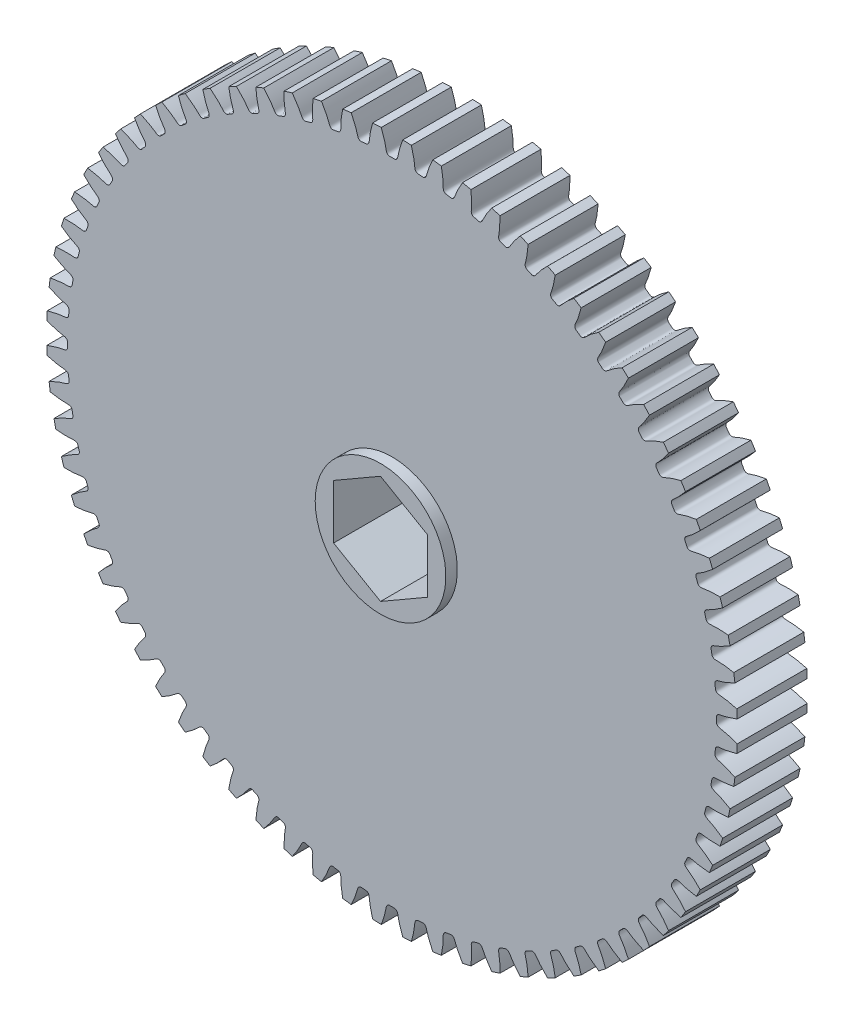
SolidWorks part; units mm, degrees
ref_plane "Front Plane" through (0, 0, 0) normal (0, 0, 1) x (1, 0, 0)
ref_plane "Top Plane" through (0, 0, 0) normal (0, 1, 0) x (1, 0, 0)
ref_plane "Right Plane" through (0, 0, 0) normal (1, 0, 0) x (0, 0, -1)
ref_plane "Plane1" through (0, 0, -4.7625) normal (0, 0, -1) x (-1, 0, 0)
sketch "Sketch1" plane through (0, 0, -4.7625) normal (0, 0, -1) x (-1, 0, 0)
  arc A0 (-46.916, 2.6363) -> (-46.9672, 1.4627) centre (0, 0) ccw
  arc A1 (-46.9672, -1.4627) -> (-46.916, -2.6363) centre (0, 0) ccw
  arc A2 (-46.661, -5.5506) -> (-46.5077, -6.7153) centre (0, 0) ccw
  arc A3 (-45.9997, -9.5963) -> (-45.7454, -10.7431) centre (0, 0) ccw
  arc A4 (-44.9883, -13.5689) -> (-44.635, -14.6892) centre (0, 0) ccw
  arc A5 (-43.6345, -17.4382) -> (-43.1849, -18.5235) centre (0, 0) ccw
  arc A6 (-41.9486, -21.1749) -> (-41.4062, -22.2169) centre (0, 0) ccw
  arc A7 (-39.9435, -24.7504) -> (-39.3123, -25.7411) centre (0, 0) ccw
  arc A8 (-37.6343, -28.1375) -> (-36.9192, -29.0694) centre (0, 0) ccw
  arc A9 (-35.0388, -31.3105) -> (-34.2451, -32.1765) centre (0, 0) ccw
  arc A10 (-32.1765, -34.2451) -> (-31.3105, -35.0388) centre (0, 0) ccw
  arc A11 (-29.0694, -36.9192) -> (-28.1375, -37.6343) centre (0, 0) ccw
  arc A12 (-25.7411, -39.3123) -> (-24.7504, -39.9435) centre (0, 0) ccw
  arc A13 (-22.2169, -41.4062) -> (-21.1749, -41.9486) centre (0, 0) ccw
  arc A14 (-18.5235, -43.1849) -> (-17.4382, -43.6345) centre (0, 0) ccw
  arc A15 (-14.6892, -44.635) -> (-13.5689, -44.9883) centre (0, 0) ccw
  arc A16 (-10.7431, -45.7454) -> (-9.5963, -45.9997) centre (0, 0) ccw
  arc A17 (-6.7153, -46.5077) -> (-5.5506, -46.661) centre (0, 0) ccw
  arc A18 (-2.6363, -46.916) -> (-1.4627, -46.9672) centre (0, 0) ccw
  arc A19 (1.4627, -46.9672) -> (2.6363, -46.916) centre (0, 0) ccw
  arc A20 (5.5506, -46.661) -> (6.7153, -46.5077) centre (0, 0) ccw
  arc A21 (9.5963, -45.9997) -> (10.7431, -45.7454) centre (0, 0) ccw
  arc A22 (13.5689, -44.9883) -> (14.6892, -44.635) centre (0, 0) ccw
  arc A23 (17.4382, -43.6345) -> (18.5235, -43.1849) centre (0, 0) ccw
  arc A24 (21.1749, -41.9486) -> (22.2169, -41.4062) centre (0, 0) ccw
  arc A25 (24.7504, -39.9435) -> (25.7411, -39.3123) centre (0, 0) ccw
  arc A26 (28.1375, -37.6343) -> (29.0694, -36.9192) centre (0, 0) ccw
  arc A27 (31.3105, -35.0388) -> (32.1765, -34.2451) centre (0, 0) ccw
  arc A28 (34.2451, -32.1765) -> (35.0388, -31.3105) centre (0, 0) ccw
  arc A29 (36.9192, -29.0694) -> (37.6343, -28.1375) centre (0, 0) ccw
  arc A30 (39.3123, -25.7411) -> (39.9435, -24.7504) centre (0, 0) ccw
  arc A31 (41.4062, -22.2169) -> (41.9486, -21.1749) centre (0, 0) ccw
  arc A32 (43.1849, -18.5235) -> (43.6345, -17.4382) centre (0, 0) ccw
  arc A33 (44.635, -14.6892) -> (44.9883, -13.5689) centre (0, 0) ccw
  arc A34 (45.7454, -10.7431) -> (45.9997, -9.5963) centre (0, 0) ccw
  arc A35 (46.5077, -6.7153) -> (46.661, -5.5506) centre (0, 0) ccw
  arc A36 (46.916, -2.6363) -> (46.9672, -1.4627) centre (0, 0) ccw
  arc A37 (46.9672, 1.4627) -> (46.916, 2.6363) centre (0, 0) ccw
  arc A38 (46.661, 5.5506) -> (46.5077, 6.7153) centre (0, 0) ccw
  arc A39 (45.9997, 9.5963) -> (45.7454, 10.7431) centre (0, 0) ccw
  arc A40 (44.9883, 13.5689) -> (44.635, 14.6892) centre (0, 0) ccw
  arc A41 (43.6345, 17.4382) -> (43.1849, 18.5235) centre (0, 0) ccw
  arc A42 (41.9486, 21.1749) -> (41.4062, 22.2169) centre (0, 0) ccw
  arc A43 (39.9435, 24.7504) -> (39.3123, 25.7411) centre (0, 0) ccw
  arc A44 (37.6343, 28.1375) -> (36.9192, 29.0694) centre (0, 0) ccw
  arc A45 (35.0388, 31.3105) -> (34.2451, 32.1765) centre (0, 0) ccw
  arc A46 (32.1765, 34.2451) -> (31.3105, 35.0388) centre (0, 0) ccw
  arc A47 (29.0694, 36.9192) -> (28.1375, 37.6343) centre (0, 0) ccw
  arc A48 (25.7411, 39.3123) -> (24.7504, 39.9435) centre (0, 0) ccw
  arc A49 (22.2169, 41.4062) -> (21.1749, 41.9486) centre (0, 0) ccw
  arc A50 (18.5235, 43.1849) -> (17.4382, 43.6345) centre (0, 0) ccw
  arc A51 (14.6892, 44.635) -> (13.5689, 44.9883) centre (0, 0) ccw
  arc A52 (10.7431, 45.7454) -> (9.5963, 45.9997) centre (0, 0) ccw
  arc A53 (6.7153, 46.5077) -> (5.5506, 46.661) centre (0, 0) ccw
  arc A54 (2.6363, 46.916) -> (1.4627, 46.9672) centre (0, 0) ccw
  arc A55 (-1.4627, 46.9672) -> (-2.6363, 46.916) centre (0, 0) ccw
  arc A56 (-5.5506, 46.661) -> (-6.7153, 46.5077) centre (0, 0) ccw
  arc A57 (-9.5963, 45.9997) -> (-10.7431, 45.7454) centre (0, 0) ccw
  arc A58 (-13.5689, 44.9883) -> (-14.6892, 44.635) centre (0, 0) ccw
  arc A59 (-17.4382, 43.6345) -> (-18.5235, 43.1849) centre (0, 0) ccw
  arc A60 (-21.1749, 41.9486) -> (-22.2169, 41.4062) centre (0, 0) ccw
  arc A61 (-24.7504, 39.9435) -> (-25.7411, 39.3123) centre (0, 0) ccw
  arc A62 (-28.1375, 37.6343) -> (-29.0694, 36.9192) centre (0, 0) ccw
  arc A63 (-31.3105, 35.0388) -> (-32.1765, 34.2451) centre (0, 0) ccw
  arc A64 (-34.2451, 32.1765) -> (-35.0388, 31.3105) centre (0, 0) ccw
  arc A65 (-36.9192, 29.0694) -> (-37.6343, 28.1375) centre (0, 0) ccw
  arc A66 (-39.3123, 25.7411) -> (-39.9435, 24.7504) centre (0, 0) ccw
  arc A67 (-41.4062, 22.2169) -> (-41.9486, 21.1749) centre (0, 0) ccw
  arc A68 (-43.1849, 18.5235) -> (-43.6345, 17.4382) centre (0, 0) ccw
  arc A69 (-44.635, 14.6892) -> (-44.9883, 13.5689) centre (0, 0) ccw
  arc A70 (-45.7454, 10.7431) -> (-45.9997, 9.5963) centre (0, 0) ccw
  arc A71 (-46.5077, 6.7153) -> (-46.661, 5.5506) centre (0, 0) ccw
  spline S0 degree 3 number of poles 73 (-46.9672, -1.4627) -> (-46.9672, 1.4627)
  spline S1 degree 3 number of poles 73 (-46.661, -5.5506) -> (-46.916, -2.6363)
  spline S2 degree 3 number of poles 73 (-45.9997, -9.5963) -> (-46.5077, -6.7153)
  spline S3 degree 3 number of poles 73 (-44.9883, -13.5689) -> (-45.7454, -10.7431)
  spline S4 degree 3 number of poles 73 (-43.6345, -17.4382) -> (-44.635, -14.6892)
  spline S5 degree 3 number of poles 73 (-41.9486, -21.1749) -> (-43.1849, -18.5235)
  spline S6 degree 3 number of poles 73 (-39.9435, -24.7504) -> (-41.4062, -22.2169)
  spline S7 degree 3 number of poles 73 (-37.6343, -28.1375) -> (-39.3123, -25.7411)
  spline S8 degree 3 number of poles 73 (-35.0388, -31.3105) -> (-36.9192, -29.0694)
  spline S9 degree 3 number of poles 73 (-32.1765, -34.2451) -> (-34.2451, -32.1765)
  spline S10 degree 3 number of poles 73 (-29.0694, -36.9192) -> (-31.3105, -35.0388)
  spline S11 degree 3 number of poles 73 (-25.7411, -39.3123) -> (-28.1375, -37.6343)
  spline S12 degree 3 number of poles 73 (-22.2169, -41.4062) -> (-24.7504, -39.9435)
  spline S13 degree 3 number of poles 73 (-18.5235, -43.1849) -> (-21.1749, -41.9486)
  spline S14 degree 3 number of poles 73 (-14.6892, -44.635) -> (-17.4382, -43.6345)
  spline S15 degree 3 number of poles 73 (-10.7431, -45.7454) -> (-13.5689, -44.9883)
  spline S16 degree 3 number of poles 73 (-6.7153, -46.5077) -> (-9.5963, -45.9997)
  spline S17 degree 3 number of poles 73 (-2.6363, -46.916) -> (-5.5506, -46.661)
  spline S18 degree 3 number of poles 73 (1.4627, -46.9672) -> (-1.4627, -46.9672)
  spline S19 degree 3 number of poles 73 (5.5506, -46.661) -> (2.6363, -46.916)
  spline S20 degree 3 number of poles 73 (9.5963, -45.9997) -> (6.7153, -46.5077)
  spline S21 degree 3 number of poles 73 (13.5689, -44.9883) -> (10.7431, -45.7454)
  spline S22 degree 3 number of poles 73 (17.4382, -43.6345) -> (14.6892, -44.635)
  spline S23 degree 3 number of poles 73 (21.1749, -41.9486) -> (18.5235, -43.1849)
  spline S24 degree 3 number of poles 73 (24.7504, -39.9435) -> (22.2169, -41.4062)
  spline S25 degree 3 number of poles 73 (28.1375, -37.6343) -> (25.7411, -39.3123)
  spline S26 degree 3 number of poles 73 (31.3105, -35.0388) -> (29.0694, -36.9192)
  spline S27 degree 3 number of poles 73 (34.2451, -32.1765) -> (32.1765, -34.2451)
  spline S28 degree 3 number of poles 73 (36.9192, -29.0694) -> (35.0388, -31.3105)
  spline S29 degree 3 number of poles 73 (39.3123, -25.7411) -> (37.6343, -28.1375)
  spline S30 degree 3 number of poles 73 (41.4062, -22.2169) -> (39.9435, -24.7504)
  spline S31 degree 3 number of poles 73 (43.1849, -18.5235) -> (41.9486, -21.1749)
  spline S32 degree 3 number of poles 73 (44.635, -14.6892) -> (43.6345, -17.4382)
  spline S33 degree 3 number of poles 73 (45.7454, -10.7431) -> (44.9883, -13.5689)
  spline S34 degree 3 number of poles 73 (46.5077, -6.7153) -> (45.9997, -9.5963)
  spline S35 degree 3 number of poles 73 (46.916, -2.6363) -> (46.661, -5.5506)
  spline S36 degree 3 number of poles 73 (46.9672, 1.4627) -> (46.9672, -1.4627)
  spline S37 degree 3 number of poles 73 (46.661, 5.5506) -> (46.916, 2.6363)
  spline S38 degree 3 number of poles 73 (45.9997, 9.5963) -> (46.5077, 6.7153)
  spline S39 degree 3 number of poles 73 (44.9883, 13.5689) -> (45.7454, 10.7431)
  spline S40 degree 3 number of poles 73 (43.6345, 17.4382) -> (44.635, 14.6892)
  spline S41 degree 3 number of poles 73 (41.9486, 21.1749) -> (43.1849, 18.5235)
  spline S42 degree 3 number of poles 73 (39.9435, 24.7504) -> (41.4062, 22.2169)
  spline S43 degree 3 number of poles 73 (37.6343, 28.1375) -> (39.3123, 25.7411)
  spline S44 degree 3 number of poles 73 (35.0388, 31.3105) -> (36.9192, 29.0694)
  spline S45 degree 3 number of poles 73 (32.1765, 34.2451) -> (34.2451, 32.1765)
  spline S46 degree 3 number of poles 73 (29.0694, 36.9192) -> (31.3105, 35.0388)
  spline S47 degree 3 number of poles 73 (25.7411, 39.3123) -> (28.1375, 37.6343)
  spline S48 degree 3 number of poles 73 (22.2169, 41.4062) -> (24.7504, 39.9435)
  spline S49 degree 3 number of poles 73 (18.5235, 43.1849) -> (21.1749, 41.9486)
  spline S50 degree 3 number of poles 73 (14.6892, 44.635) -> (17.4382, 43.6345)
  spline S51 degree 3 number of poles 73 (10.7431, 45.7454) -> (13.5689, 44.9883)
  spline S52 degree 3 number of poles 73 (6.7153, 46.5077) -> (9.5963, 45.9997)
  spline S53 degree 3 number of poles 73 (2.6363, 46.916) -> (5.5506, 46.661)
  spline S54 degree 3 number of poles 73 (-1.4627, 46.9672) -> (1.4627, 46.9672)
  spline S55 degree 3 number of poles 73 (-5.5506, 46.661) -> (-2.6363, 46.916)
  spline S56 degree 3 number of poles 73 (-9.5963, 45.9997) -> (-6.7153, 46.5077)
  spline S57 degree 3 number of poles 73 (-13.5689, 44.9883) -> (-10.7431, 45.7454)
  spline S58 degree 3 number of poles 73 (-17.4382, 43.6345) -> (-14.6892, 44.635)
  spline S59 degree 3 number of poles 73 (-21.1749, 41.9486) -> (-18.5235, 43.1849)
  spline S60 degree 3 number of poles 73 (-24.7504, 39.9435) -> (-22.2169, 41.4062)
  spline S61 degree 3 number of poles 73 (-28.1375, 37.6343) -> (-25.7411, 39.3123)
  spline S62 degree 3 number of poles 73 (-31.3105, 35.0388) -> (-29.0694, 36.9192)
  spline S63 degree 3 number of poles 73 (-34.2451, 32.1765) -> (-32.1765, 34.2451)
  spline S64 degree 3 number of poles 73 (-36.9192, 29.0694) -> (-35.0388, 31.3105)
  spline S65 degree 3 number of poles 73 (-39.3123, 25.7411) -> (-37.6343, 28.1375)
  spline S66 degree 3 number of poles 73 (-41.4062, 22.2169) -> (-39.9435, 24.7504)
  spline S67 degree 3 number of poles 73 (-43.1849, 18.5235) -> (-41.9486, 21.1749)
  spline S68 degree 3 number of poles 73 (-44.635, 14.6892) -> (-43.6345, 17.4382)
  spline S69 degree 3 number of poles 73 (-45.7454, 10.7431) -> (-44.9883, 13.5689)
  spline S70 degree 3 number of poles 73 (-46.5077, 6.7153) -> (-45.9997, 9.5963)
  spline S71 degree 3 number of poles 73 (-46.916, 2.6363) -> (-46.661, 5.5506)
extrude "Boss-Extrude1" add sketch "Sketch1" against normal blind 9.525
sketch "Sketch2" plane through (0, 0, -4.7625) normal (0, 0, -1) x (-1, 0, 0)
  circle A0 centre (0, 0) radius 8.89
extrude "Boss-Extrude2" add sketch "Sketch2" along normal blind 1.5621
sketch "Sketch3" plane through (0, 0, 4.7625) normal (0, 0, 1) x (1, 0, 0)
  circle A0 centre (0, 0) radius 8.89
extrude "Boss-Extrude3" add sketch "Sketch3" along normal blind 1.5621
sketch "Sketch4" plane through (0, 0, 6.3246) normal (0, 0, 1) x (1, 0, 0)
  line L0 (6.3881, -3.6882) -> (6.3881, 3.6882)
  line L1 (6.3881, 3.6882) -> (0, 7.3763)
  line L2 (0, 7.3763) -> (-6.3881, 3.6882)
  line L3 (-6.3881, 3.6882) -> (-6.3881, -3.6882)
  line L4 (-6.3881, -3.6882) -> (0, -7.3763)
  line L5 (0, -7.3763) -> (6.3881, -3.6882)
extrude "Cut-Extrude1" cut sketch "Sketch4" against normal through all
